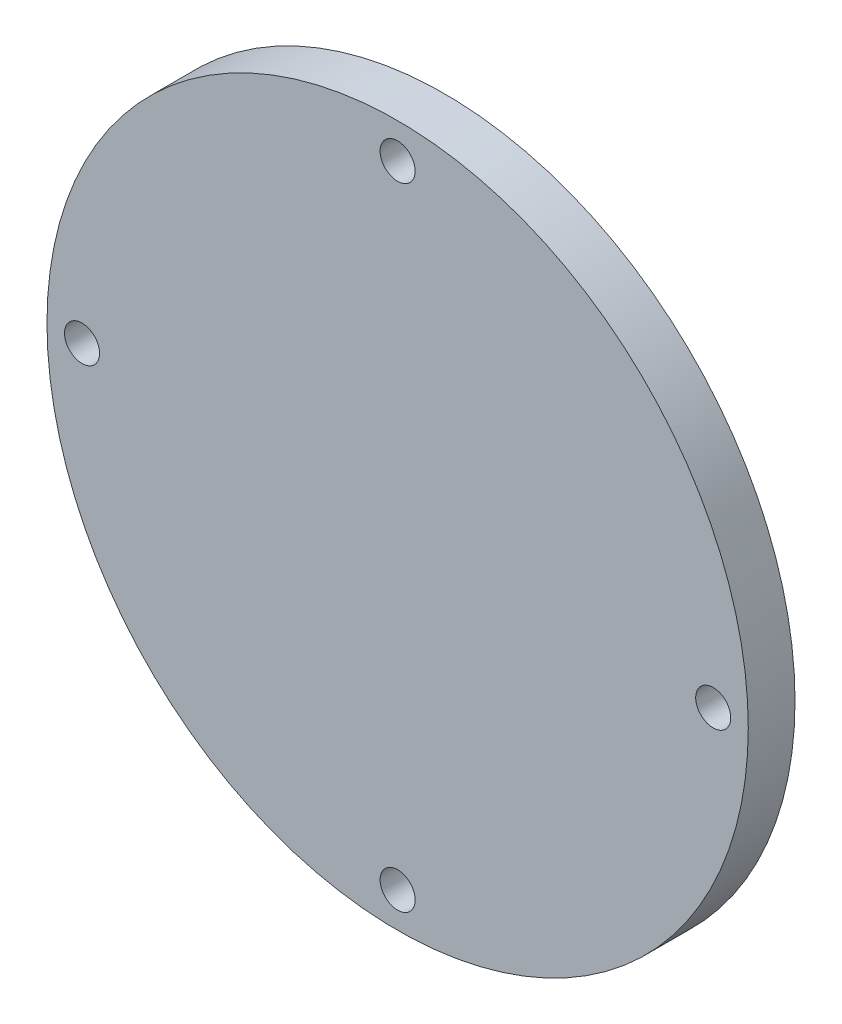
SolidWorks part; units mm, degrees
material "1060 合金"
ref_plane "前视基准面" through (0, 0, 0) normal (0, 0, 1) x (1, 0, 0)
ref_plane "上视基准面" through (0, 0, 0) normal (0, 1, 0) x (1, 0, 0)
ref_plane "右视基准面" through (0, 0, 0) normal (1, 0, 0) x (0, 0, -1)
sketch "草图1" plane through (0, 0, 0) normal (0, 0, 1) x (1, 0, 0)
  circle A0 centre (0, 0) radius 30
extrude "凸台-拉伸1" add sketch "草图1" along normal blind 4
sketch "草图3" plane through (0, 0, 4) normal (0, 0, 1) x (1, 0, 0)
  circle A0 centre (0, 27) radius 1.5
extrude "切除-拉伸1" cut sketch "草图3" against normal blind 10
pattern_circular "阵列(圆周)1" count 4 over 360 about axis through (0, 0, 0) along (0, 0, 1) of "切除-拉伸1"
sketch "草图4" plane through (0, 0, 0) normal (0, 0, -1) x (-1, 0, 0)
  circle A0 centre (0, 0) radius 16
  circle A1 centre (0, 0) radius 12.5
extrude "凸台-拉伸2" add sketch "草图4" along normal blind 6
fillet "圆角1" [suppressed] radius 0.3
